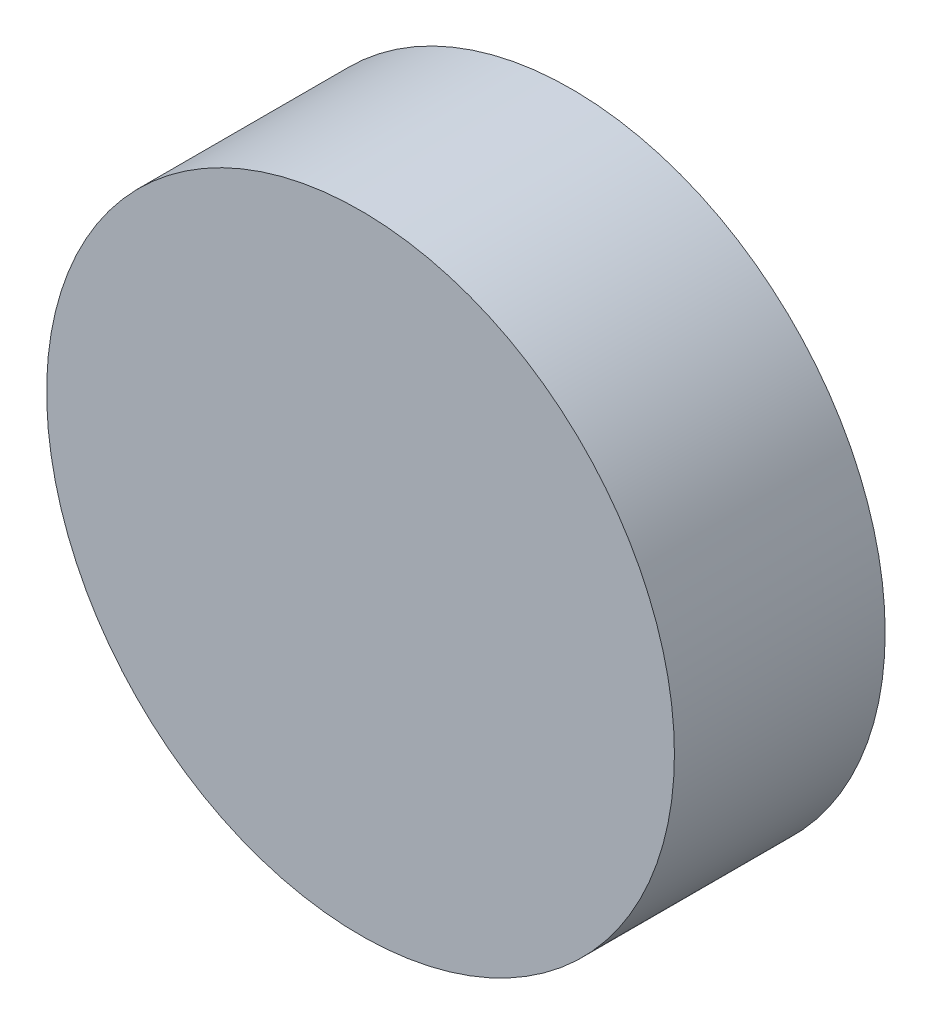
SolidWorks part; units mm, degrees
ref_plane "Front Plane" through (0, 0, 0) normal (0, 0, 1) x (1, 0, 0)
ref_plane "Top Plane" through (0, 0, 0) normal (0, 1, 0) x (1, 0, 0)
ref_plane "Right Plane" through (0, 0, 0) normal (1, 0, 0) x (0, 0, -1)
sketch "Sketch1" plane through (0, 0, 0) normal (0, 0, 1) x (1, 0, 0)
  circle A0 centre (0, 0) radius 14
  dimension "D1" = 28
extrude "Boss-Extrude1" add sketch "Sketch1" along normal blind 9.4 contours A0
